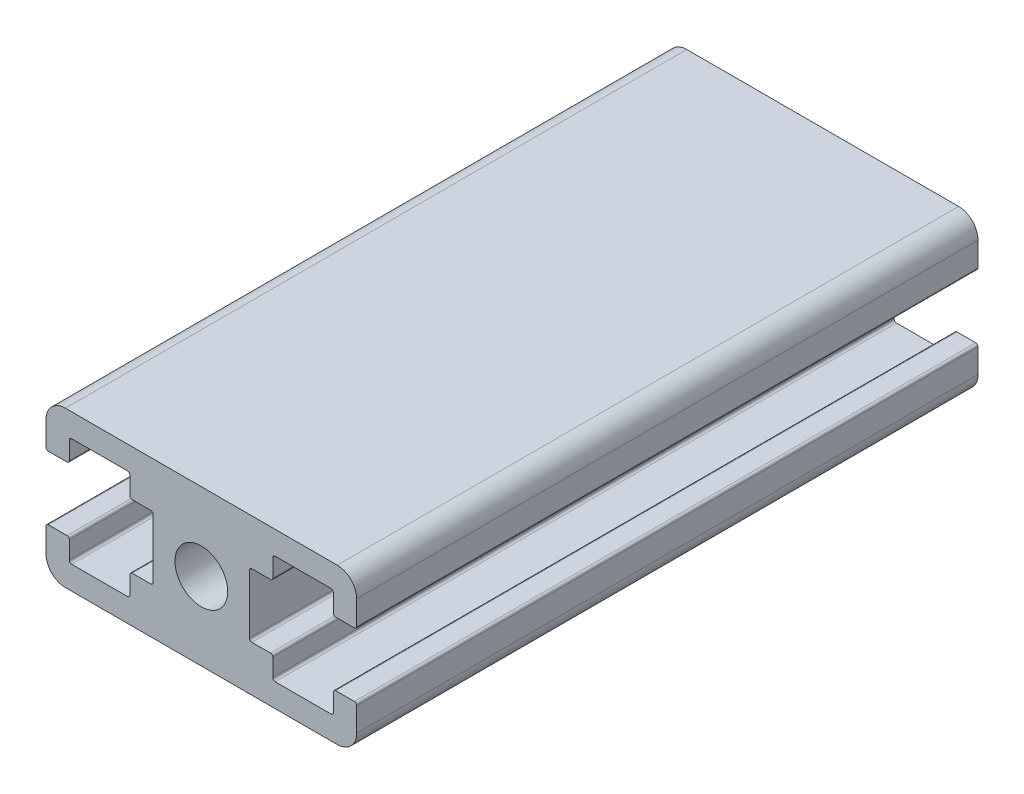
SolidWorks part; units mm, degrees
ref_plane "前视基准面" through (0, 0, 0) normal (0, 0, 1) x (1, 0, 0)
ref_plane "上视基准面" through (0, 0, 0) normal (0, 1, 0) x (1, 0, 0)
ref_plane "右视基准面" through (0, 0, 0) normal (1, 0, 0) x (0, 0, -1)
sketch "草图1" plane through (0, 0, 0) normal (0, 0, 1) x (1, 0, 0)
  line L0 (20.2298, 4.0553) -> (20.2298, 7.1553)
  line L1 (17.7298, 9.6553) -> (-17.2702, 9.6553)
  line L2 (-19.7702, 7.1553) -> (-19.7702, 4.0553)
  line L3 (-19.4702, 3.7553) -> (-17.0702, 3.7553)
  line L4 (-16.7702, 4.0553) -> (-16.7702, 6.3553)
  line L5 (-16.4702, 6.6553) -> (-9.2702, 6.6553)
  line L6 (-8.9702, 6.3553) -> (-8.9702, 4.0553)
  line L7 (-8.6702, 3.7553) -> (-6.2702, 3.7553)
  line L8 (-5.9702, 3.4553) -> (-5.9702, -4.1447)
  line L9 (-6.2702, -4.4447) -> (-8.6702, -4.4447)
  line L10 (-8.9702, -4.7447) -> (-8.9702, -7.0447)
  line L11 (-9.2702, -7.3447) -> (-16.4702, -7.3447)
  line L12 (19.9298, 3.7553) -> (17.5298, 3.7553)
  line L13 (17.2298, 4.0553) -> (17.2298, 6.3553)
  line L14 (16.9298, 6.6553) -> (9.7298, 6.6553)
  line L15 (9.4298, 6.3553) -> (9.4298, 4.0553)
  line L16 (9.1298, 3.7553) -> (6.7298, 3.7553)
  line L17 (6.4298, 3.4553) -> (6.4298, -4.1447)
  line L18 (6.7298, -4.4447) -> (9.1298, -4.4447)
  line L19 (9.4298, -4.7447) -> (9.4298, -7.0447)
  line L20 (9.7298, -7.3447) -> (16.9298, -7.3447)
  line L21 (17.2298, -7.0447) -> (17.2298, -4.7447)
  line L22 (17.5298, -4.4447) -> (19.9298, -4.4447)
  line L23 (20.2298, -4.7447) -> (20.2298, -7.8447)
  line L24 (17.7298, -10.3447) -> (-17.2702, -10.3447)
  line L25 (-19.7702, -7.8447) -> (-19.7702, -4.7447)
  line L26 (-19.4702, -4.4447) -> (-17.0702, -4.4447)
  line L27 (-16.7702, -4.7447) -> (-16.7702, -7.0447)
  arc A0 (20.2298, 7.1553) -> (17.7298, 9.6553) centre (17.7298, 7.1553) ccw
  arc A1 (-17.2702, 9.6553) -> (-19.7702, 7.1553) centre (-17.2702, 7.1553) ccw
  arc A2 (-19.7702, 4.0553) -> (-19.4702, 3.7553) centre (-19.4702, 4.0553) ccw
  arc A3 (-17.0702, 3.7553) -> (-16.7702, 4.0553) centre (-17.0702, 4.0553) ccw
  arc A4 (-16.4702, 6.6553) -> (-16.7702, 6.3553) centre (-16.4702, 6.3553) ccw
  arc A5 (-8.9702, 6.3553) -> (-9.2702, 6.6553) centre (-9.2702, 6.3553) ccw
  arc A6 (-8.9702, 4.0553) -> (-8.6702, 3.7553) centre (-8.6702, 4.0553) ccw
  arc A7 (-5.9702, 3.4553) -> (-6.2702, 3.7553) centre (-6.2702, 3.4553) ccw
  arc A8 (-6.2702, -4.4447) -> (-5.9702, -4.1447) centre (-6.2702, -4.1447) ccw
  arc A9 (-8.6702, -4.4447) -> (-8.9702, -4.7447) centre (-8.6702, -4.7447) ccw
  arc A10 (-9.2702, -7.3447) -> (-8.9702, -7.0447) centre (-9.2702, -7.0447) ccw
  arc A11 (17.2298, 4.0553) -> (17.5298, 3.7553) centre (17.5298, 4.0553) ccw
  arc A12 (17.2298, 6.3553) -> (16.9298, 6.6553) centre (16.9298, 6.3553) ccw
  arc A13 (9.7298, 6.6553) -> (9.4298, 6.3553) centre (9.7298, 6.3553) ccw
  arc A14 (9.1298, 3.7553) -> (9.4298, 4.0553) centre (9.1298, 4.0553) ccw
  arc A15 (6.7298, 3.7553) -> (6.4298, 3.4553) centre (6.7298, 3.4553) ccw
  arc A16 (6.4298, -4.1447) -> (6.7298, -4.4447) centre (6.7298, -4.1447) ccw
  arc A17 (9.4298, -4.7447) -> (9.1298, -4.4447) centre (9.1298, -4.7447) ccw
  arc A18 (9.4298, -7.0447) -> (9.7298, -7.3447) centre (9.7298, -7.0447) ccw
  arc A19 (16.9298, -7.3447) -> (17.2298, -7.0447) centre (16.9298, -7.0447) ccw
  arc A20 (17.5298, -4.4447) -> (17.2298, -4.7447) centre (17.5298, -4.7447) ccw
  arc A21 (20.2298, -4.7447) -> (19.9298, -4.4447) centre (19.9298, -4.7447) ccw
  arc A22 (17.7298, -10.3447) -> (20.2298, -7.8447) centre (17.7298, -7.8447) ccw
  arc A23 (-19.7702, -7.8447) -> (-17.2702, -10.3447) centre (-17.2702, -7.8447) ccw
  arc A24 (-19.4702, -4.4447) -> (-19.7702, -4.7447) centre (-19.4702, -4.7447) ccw
  arc A25 (-16.7702, -4.7447) -> (-17.0702, -4.4447) centre (-17.0702, -4.7447) ccw
  arc A26 (-16.7702, -7.0447) -> (-16.4702, -7.3447) centre (-16.4702, -7.0447) ccw
  arc A27 (19.9298, 3.7553) -> (20.2298, 4.0553) centre (19.9298, 4.0553) ccw
  circle A28 centre (0.2298, -0.3447) radius 3.4
extrude "凸台-拉伸1" add sketch "草图1" along normal blind 80
